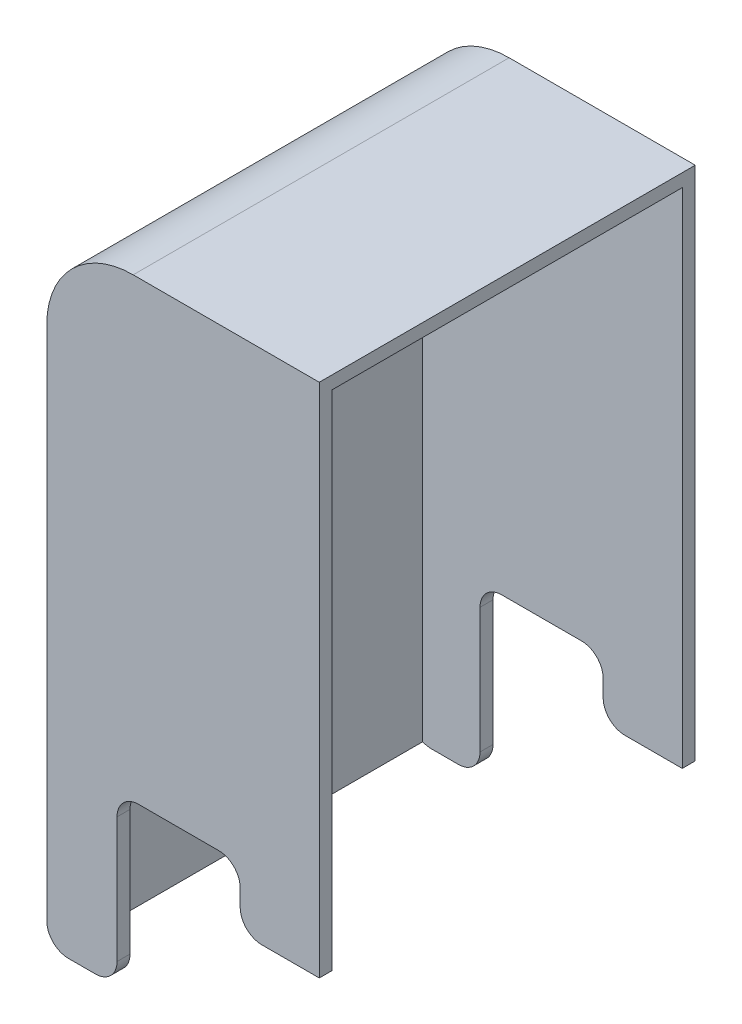
SolidWorks part; units mm, degrees
ref_plane "Front Plane" through (0, 0, 0) normal (0, 0, 1) x (1, 0, 0)
ref_plane "Top Plane" through (0, 0, 0) normal (0, 1, 0) x (1, 0, 0)
ref_plane "Right Plane" through (0, 0, 0) normal (1, 0, 0) x (0, 0, -1)
sketch "Sketch1" plane through (0, 0, 0) normal (0, 0, 1) x (1, 0, 0)
  line L0 (31.56, -47.5063) -> (31.56, 71.8937)
  line L1 (16.2955, 36.8937) -> (16.2955, 61.8937) construction
  line L2 (31.56, 71.8937) -> (-11.5, 71.8937)
  line L3 (-31.5, 51.8937) -> (-31.5, -67.6063)
  line L4 (-26.5, -72.6063) -> (-20.24, -72.6063)
  line L5 (-15.24, -67.6063) -> (-15.24, -38.6063)
  line L6 (-10.24, -33.6063) -> (8.26, -33.6063)
  line L7 (13.26, -38.6063) -> (13.26, -42.5063)
  line L8 (18.26, -47.5063) -> (31.56, -47.5063)
  arc A0 (-11.5, 71.8937) -> (-31.5, 51.8937) centre (-11.5, 51.8937) ccw
  arc A1 (13.26, -42.5063) -> (18.26, -47.5063) centre (18.26, -42.5063) ccw
  arc A2 (8.26, -33.6063) -> (13.26, -38.6063) centre (8.26, -38.6063) cw
  arc A3 (-15.24, -38.6063) -> (-10.24, -33.6063) centre (-10.24, -38.6063) cw
  arc A4 (-31.5, -67.6063) -> (-26.5, -72.6063) centre (-26.5, -67.6063) ccw
  arc A5 (-20.24, -72.6063) -> (-15.24, -67.6063) centre (-20.24, -67.6063) ccw
  point P12 (-31.5, 71.8937)
  point P15 (13.26, -47.5063)
  point P18 (13.26, -33.6063)
  point P21 (-15.24, -33.6063)
  point P24 (-31.5, -72.6063)
  point P27 (-15.24, -72.6063)
  dimension "D9" = 20
  dimension "D10" = 5
  dimension "D11" = 5
  dimension "D1" = 25
  dimension "D2" = 144.5
  dimension "D3" = 16.26
  dimension "D4" = 39
  dimension "D5" = 28.5
  dimension "D6" = 13.9
  dimension "D7" = 18.3
  dimension "D8" = 63.06
extrude "Boss-Extrude1" add sketch "Sketch1" along normal mid plane 3
sketch "Sketch2" plane through (0, 0, -1.5) normal (0, 0, -1) x (-1, 0, 0)
  line L13 (28.5, -67.6063) -> (28.5, 51.8937)
  line L14 (11.5, 68.8937) -> (-28.56, 68.8937)
  line L16 (-31.56, -47.5063) -> (-18.26, -47.5063)
  line L17 (-13.26, -42.5063) -> (-13.26, -38.6063)
  line L18 (-8.26, -33.6063) -> (10.24, -33.6063)
  line L19 (15.24, -38.6063) -> (15.24, -67.6063)
  line L20 (20.24, -72.6063) -> (26.5, -72.6063)
  line L21 (31.5, -67.6063) -> (31.5, 51.8937)
  line L22 (11.5, 71.8937) -> (-31.56, 71.8937)
  line L23 (-31.56, 71.8937) -> (-31.56, -47.5063)
  line L29 (31.5, -67.6063) -> (31.5, 51.8937)
  line L30 (11.5, 71.8937) -> (-31.56, 71.8937)
  line L31 (-31.56, 71.8937) -> (-31.56, 68.8937)
  line L32 (-28.56, 68.8937) -> (-31.56, 68.8937)
  line L33 (28.5, -67.6063) -> (28.5, -72.1888)
  line L34 (-31.56, 71.8937) -> (-31.56, -47.5063) construction
  line L35 (20.24, -72.6063) -> (26.5, -72.6063) construction
  line L36 (20.24, -69.6063) -> (26.5, -69.6063) construction
  line L37 (18.24, -38.6063) -> (18.24, -67.6063) construction
  line L38 (15.24, -38.6063) -> (15.24, -67.6063) construction
  line L39 (-8.26, -33.6063) -> (10.24, -33.6063) construction
  line L40 (-8.26, -30.6063) -> (10.24, -30.6063) construction
  line L41 (-13.26, -42.5063) -> (-13.26, -38.6063) construction
  line L42 (-16.26, -42.5063) -> (-16.26, -38.6063) construction
  line L43 (-31.56, -47.5063) -> (-18.26, -47.5063) construction
  line L44 (-28.56, -44.5063) -> (-18.26, -44.5063) construction
  line L45 (-28.56, 68.8937) -> (-28.56, -44.5063) construction
  arc A11 (28.5, 51.8937) -> (11.5, 68.8937) centre (11.5, 51.8937) ccw
  arc A12 (-18.26, -47.5063) -> (-13.26, -42.5063) centre (-18.26, -42.5063) ccw
  arc A13 (-8.26, -33.6063) -> (-13.26, -38.6063) centre (-8.26, -38.6063) ccw
  arc A14 (15.24, -38.6063) -> (10.24, -33.6063) centre (10.24, -38.6063) ccw
  arc A15 (15.24, -67.6063) -> (20.24, -72.6063) centre (20.24, -67.6063) ccw
  arc A16 (26.5, -72.6063) -> (31.5, -67.6063) centre (26.5, -67.6063) ccw
  arc A17 (31.5, 51.8937) -> (11.5, 71.8937) centre (11.5, 51.8937) ccw
  arc A22 (28.5, -72.1888) -> (31.5, -67.6063) centre (26.5, -67.6063) ccw
  arc A23 (31.5, 51.8937) -> (11.5, 71.8937) centre (11.5, 51.8937) ccw
  arc A24 (26.5, -69.6063) -> (28.5, -67.6063) centre (26.5, -67.6063) ccw construction
  arc A25 (26.5, -72.6063) -> (31.5, -67.6063) centre (26.5, -67.6063) ccw construction
  arc A26 (15.24, -67.6063) -> (20.24, -72.6063) centre (20.24, -67.6063) ccw construction
  arc A27 (18.24, -67.6063) -> (20.24, -69.6063) centre (20.24, -67.6063) ccw construction
  arc A28 (15.24, -38.6063) -> (10.24, -33.6063) centre (10.24, -38.6063) ccw construction
  arc A29 (18.24, -38.6063) -> (10.24, -30.6063) centre (10.24, -38.6063) ccw construction
  arc A30 (-8.26, -30.6063) -> (-16.26, -38.6063) centre (-8.26, -38.6063) ccw construction
  arc A31 (-8.26, -33.6063) -> (-13.26, -38.6063) centre (-8.26, -38.6063) ccw construction
  arc A32 (-18.26, -44.5063) -> (-16.26, -42.5063) centre (-18.26, -42.5063) ccw construction
  arc A33 (-18.26, -47.5063) -> (-13.26, -42.5063) centre (-18.26, -42.5063) ccw construction
  dimension "D1" = 0
  dimension "D2" = 3
extrude "Boss-Extrude2" add sketch "Sketch2" along normal blind 81
sketch "Sketch3" plane through (0, 0, -82.5) normal (0, 0, -1) x (-1, 0, 0)
  line L67 (-31.56, 68.8937) -> (-31.56, 71.8937)
  line L75 (-31.56, 68.8937) -> (-31.56, -47.5063)
  line L76 (-31.56, -47.5063) -> (-18.26, -47.5063)
  line L77 (-13.26, -42.5063) -> (-13.26, -38.6063)
  line L78 (-8.26, -33.6063) -> (10.24, -33.6063)
  line L79 (15.24, -38.6063) -> (15.24, -67.6063)
  line L80 (20.24, -72.6063) -> (26.5, -72.6063)
  line L81 (31.5, -67.6063) -> (31.5, 51.8937)
  line L82 (11.5, 71.8937) -> (-31.56, 71.8937)
  line L83 (-31.56, 68.8937) -> (-31.56, -47.5063)
  line L84 (-31.56, -47.5063) -> (-18.26, -47.5063)
  line L85 (-13.26, -42.5063) -> (-13.26, -38.6063)
  line L86 (-8.26, -33.6063) -> (10.24, -33.6063)
  line L87 (15.24, -38.6063) -> (15.24, -67.6063)
  line L88 (20.24, -72.6063) -> (26.5, -72.6063)
  line L89 (31.5, -67.6063) -> (31.5, 51.8937)
  line L90 (11.5, 71.8937) -> (-31.56, 71.8937)
  arc A74 (-18.26, -47.5063) -> (-13.26, -42.5063) centre (-18.26, -42.5063) ccw
  arc A75 (-8.26, -33.6063) -> (-13.26, -38.6063) centre (-8.26, -38.6063) ccw
  arc A76 (15.24, -38.6063) -> (10.24, -33.6063) centre (10.24, -38.6063) ccw
  arc A77 (15.24, -67.6063) -> (20.24, -72.6063) centre (20.24, -67.6063) ccw
  arc A78 (26.5, -72.6063) -> (28.5, -72.1888) centre (26.5, -67.6063) ccw
  arc A79 (28.5, -72.1888) -> (31.5, -67.6063) centre (26.5, -67.6063) ccw
  arc A80 (31.5, 51.8937) -> (11.5, 71.8937) centre (11.5, 51.8937) ccw
  arc A81 (-18.26, -47.5063) -> (-13.26, -42.5063) centre (-18.26, -42.5063) ccw
  arc A82 (-8.26, -33.6063) -> (-13.26, -38.6063) centre (-8.26, -38.6063) ccw
  arc A83 (15.24, -38.6063) -> (10.24, -33.6063) centre (10.24, -38.6063) ccw
  arc A84 (15.24, -67.6063) -> (20.24, -72.6063) centre (20.24, -67.6063) ccw
  arc A85 (26.5, -72.6063) -> (28.5, -72.1888) centre (26.5, -67.6063) ccw
  arc A86 (28.5, -72.1888) -> (31.5, -67.6063) centre (26.5, -67.6063) ccw
  arc A87 (31.5, 51.8937) -> (11.5, 71.8937) centre (11.5, 51.8937) ccw
  dimension "D1" = 0
extrude "Boss-Extrude3" add sketch "Sketch3" along normal blind 3
